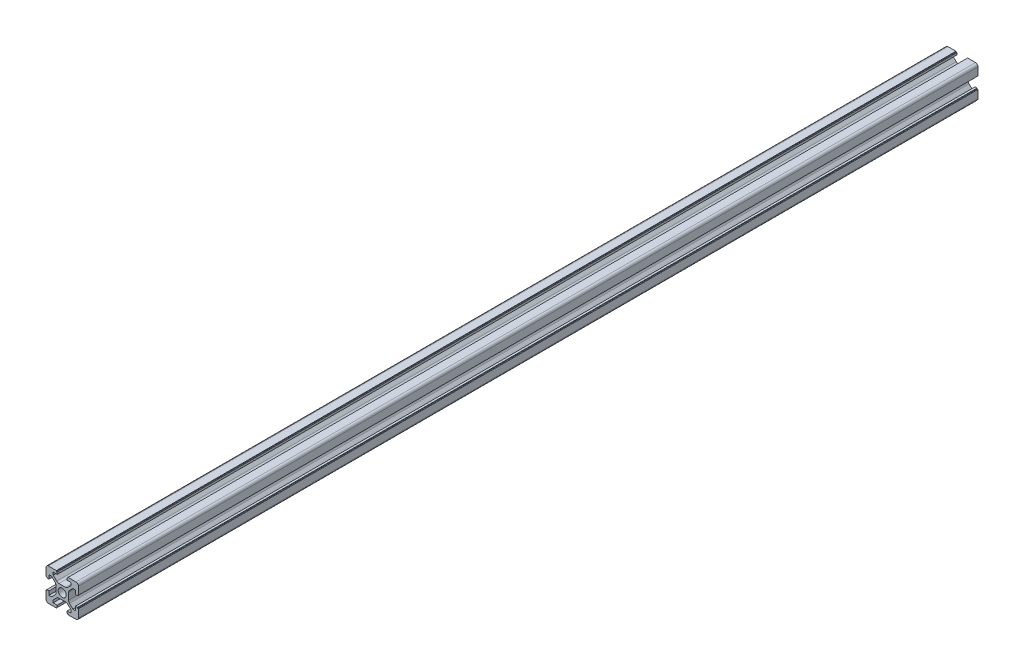
SolidWorks part; units mm, degrees
ref_plane "Спереди" through (0, 0, 0) normal (0, 0, 1) x (1, 0, 0)
ref_plane "Сверху" through (0, 0, 0) normal (0, 1, 0) x (1, 0, 0)
ref_plane "Справа" through (0, 0, 0) normal (1, 0, 0) x (0, 0, -1)
sketch "Sketch1" plane through (0, 0, 0) normal (0, 0, 1) x (1, 0, 0)
  line L0 (0, 10) -> (0, -10) construction
  line L1 (-10, -10) -> (10, -10) construction
  line L2 (-10, -10) -> (-10, 10) construction
  line L3 (-10, 10) -> (10, 10) construction
  line L4 (10, -10) -> (10, 10) construction
  line L5 (-10, -10) -> (10, 10) construction
  line L6 (-10, 10) -> (10, -10) construction
  line L7 (-10, 0) -> (10, 0) construction
  line L8 (0, 3.9) -> (-2.0109, 3.9)
  line L9 (-3.4251, 4.4858) -> (-5.5393, 6.6)
  line L10 (-5.5393, 6.6) -> (-5.5393, 8.2)
  line L11 (-5.5393, 8.2) -> (-3.1, 8.2)
  line L12 (-3.1, 8.2) -> (-3.1, 9.5)
  line L13 (-3.1, 9.5) -> (-3.4, 9.5)
  line L14 (-3.6, 9.7) -> (-3.6, 10)
  line L15 (-3.6, 10) -> (-8.5, 10)
  line L16 (-10, 3.6) -> (-10, 8.5)
  line L17 (-9.7, 3.6) -> (-10, 3.6)
  line L18 (-9.5, 3.1) -> (-9.5, 3.4)
  line L19 (-8.2, 3.1) -> (-9.5, 3.1)
  line L20 (-8.2, 5.5393) -> (-8.2, 3.1)
  line L21 (-6.6, 5.5393) -> (-8.2, 5.5393)
  line L22 (-4.4858, 3.4251) -> (-6.6, 5.5393)
  line L23 (-3.9, 0) -> (-3.9, 2.0109)
  line L24 (3.9, 0) -> (3.9, 2.0109)
  line L25 (4.4858, 3.4251) -> (6.6, 5.5393)
  line L26 (6.6, 5.5393) -> (8.2, 5.5393)
  line L27 (8.2, 5.5393) -> (8.2, 3.1)
  line L28 (8.2, 3.1) -> (9.5, 3.1)
  line L29 (9.5, 3.1) -> (9.5, 3.4)
  line L30 (9.7, 3.6) -> (10, 3.6)
  line L31 (10, 3.6) -> (10, 8.5)
  line L32 (3.6, 10) -> (8.5, 10)
  line L33 (3.6, 9.7) -> (3.6, 10)
  line L34 (3.1, 9.5) -> (3.4, 9.5)
  line L35 (3.1, 8.2) -> (3.1, 9.5)
  line L36 (5.5393, 8.2) -> (3.1, 8.2)
  line L37 (5.5393, 6.6) -> (5.5393, 8.2)
  line L38 (3.4251, 4.4858) -> (5.5393, 6.6)
  line L39 (0, 3.9) -> (2.0109, 3.9)
  line L40 (0, -3.9) -> (2.0109, -3.9)
  line L41 (3.4251, -4.4858) -> (5.5393, -6.6)
  line L42 (5.5393, -6.6) -> (5.5393, -8.2)
  line L43 (5.5393, -8.2) -> (3.1, -8.2)
  line L44 (3.1, -8.2) -> (3.1, -9.5)
  line L45 (3.1, -9.5) -> (3.4, -9.5)
  line L46 (3.6, -9.7) -> (3.6, -10)
  line L47 (3.6, -10) -> (8.5, -10)
  line L48 (10, -3.6) -> (10, -8.5)
  line L49 (9.7, -3.6) -> (10, -3.6)
  line L50 (9.5, -3.1) -> (9.5, -3.4)
  line L51 (8.2, -3.1) -> (9.5, -3.1)
  line L52 (8.2, -5.5393) -> (8.2, -3.1)
  line L53 (6.6, -5.5393) -> (8.2, -5.5393)
  line L54 (4.4858, -3.4251) -> (6.6, -5.5393)
  line L55 (3.9, 0) -> (3.9, -2.0109)
  line L56 (-3.9, 0) -> (-3.9, -2.0109)
  line L57 (-4.4858, -3.4251) -> (-6.6, -5.5393)
  line L58 (-6.6, -5.5393) -> (-8.2, -5.5393)
  line L59 (-8.2, -5.5393) -> (-8.2, -3.1)
  line L60 (-8.2, -3.1) -> (-9.5, -3.1)
  line L61 (-9.5, -3.1) -> (-9.5, -3.4)
  line L62 (-9.7, -3.6) -> (-10, -3.6)
  line L63 (-10, -3.6) -> (-10, -8.5)
  line L64 (-3.6, -10) -> (-8.5, -10)
  line L65 (-3.6, -9.7) -> (-3.6, -10)
  line L66 (-3.1, -9.5) -> (-3.4, -9.5)
  line L67 (-3.1, -8.2) -> (-3.1, -9.5)
  line L68 (-5.5393, -8.2) -> (-3.1, -8.2)
  line L69 (-5.5393, -6.6) -> (-5.5393, -8.2)
  line L70 (-3.4251, -4.4858) -> (-5.5393, -6.6)
  line L71 (0, -3.9) -> (-2.0109, -3.9)
  circle A0 centre (0, 0) radius 2.5
  arc A1 (-8.5, 10) -> (-10, 8.5) centre (-8.5, 8.5) ccw
  arc A2 (-2.0109, 3.9) -> (-3.4251, 4.4858) centre (-2.0109, 5.9) cw
  arc A3 (-3.4, 9.5) -> (-3.6, 9.7) centre (-3.4, 9.7) cw
  arc A4 (-9.5, 3.4) -> (-9.7, 3.6) centre (-9.7, 3.4) ccw
  arc A5 (-3.9, 2.0109) -> (-4.4858, 3.4251) centre (-5.9, 2.0109) ccw
  arc A6 (10, 8.5) -> (8.5, 10) centre (8.5, 8.5) ccw
  arc A7 (3.9, 2.0109) -> (4.4858, 3.4251) centre (5.9, 2.0109) cw
  arc A8 (9.5, 3.4) -> (9.7, 3.6) centre (9.7, 3.4) cw
  arc A9 (3.4, 9.5) -> (3.6, 9.7) centre (3.4, 9.7) ccw
  arc A10 (2.0109, 3.9) -> (3.4251, 4.4858) centre (2.0109, 5.9) ccw
  arc A11 (8.5, -10) -> (10, -8.5) centre (8.5, -8.5) ccw
  arc A12 (2.0109, -3.9) -> (3.4251, -4.4858) centre (2.0109, -5.9) cw
  arc A13 (3.4, -9.5) -> (3.6, -9.7) centre (3.4, -9.7) cw
  arc A14 (9.5, -3.4) -> (9.7, -3.6) centre (9.7, -3.4) ccw
  arc A15 (3.9, -2.0109) -> (4.4858, -3.4251) centre (5.9, -2.0109) ccw
  arc A16 (-10, -8.5) -> (-8.5, -10) centre (-8.5, -8.5) ccw
  arc A17 (-3.9, -2.0109) -> (-4.4858, -3.4251) centre (-5.9, -2.0109) cw
  arc A18 (-9.5, -3.4) -> (-9.7, -3.6) centre (-9.7, -3.4) cw
  arc A19 (-3.4, -9.5) -> (-3.6, -9.7) centre (-3.4, -9.7) ccw
  arc A20 (-2.0109, -3.9) -> (-3.4251, -4.4858) centre (-2.0109, -5.9) ccw
  point P0 (0, 0)
  point P42 (0, 0)
  point P70 (0, 0)
  point P98 (0, 0)
  point P126 (0, 0)
  dimension "D3" = 5
  dimension "D4" = 3
  dimension "D12" = 2
  dimension "D13" = 0.2
  dimension "D1" = 20
  dimension "D2" = 20
  dimension "D5" = 6.2
  dimension "D6" = 7.2
  dimension "D7" = 1.8
  dimension "D8" = 0.5
  dimension "D9" = 3.4
  dimension "D10" = 1.5
  dimension "D11" = 6.1
  dimension "D14" = 4
extrude "Extrude1" add sketch "Sketch1" along normal blind 555
